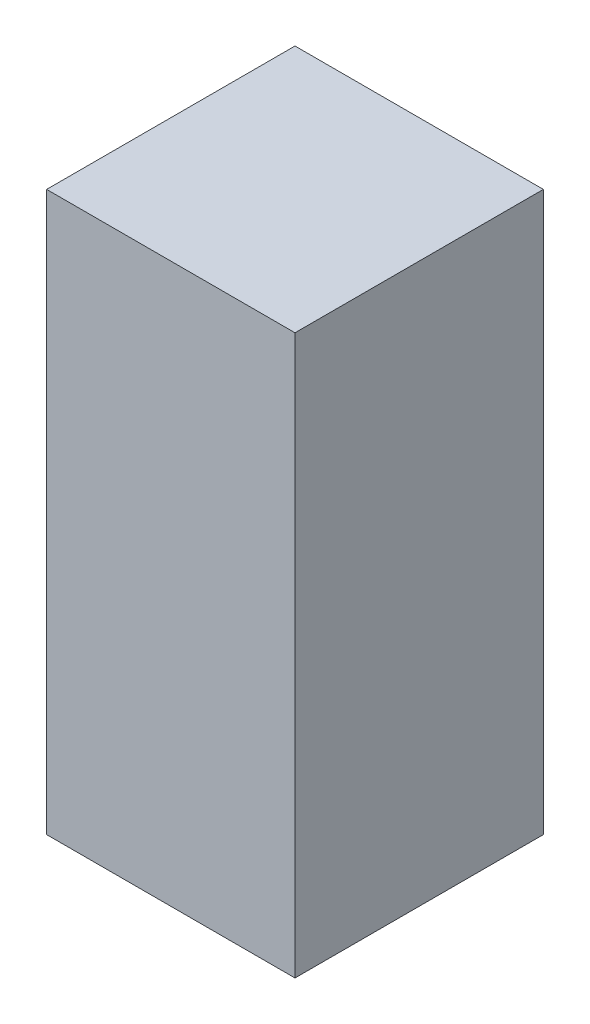
SolidWorks part; units mm, degrees
ref_plane "Front Plane" through (0, 0, 0) normal (0, 0, 1) x (1, 0, 0)
ref_plane "Top Plane" through (0, 0, 0) normal (0, 1, 0) x (1, 0, 0)
ref_plane "Right Plane" through (0, 0, 0) normal (1, 0, 0) x (0, 0, -1)
sketch "Sketch1" plane through (0, 0, 0) normal (0, 1, 0) x (1, 0, 0)
  line L1 (50, -50) -> (-50, -50)
  line L2 (50, -50) -> (50, 50)
  line L3 (50, 50) -> (-50, 50)
  line L4 (-50, -50) -> (-50, 50)
  line L5 (50, -50) -> (-50, 50) construction
  line L6 (50, 50) -> (-50, -50) construction
  point P0 (0, 0)
  dimension "D1" = 100
  dimension "D2" = 100
extrude "Boss-Extrude1" add sketch "Sketch1" along normal blind 225
